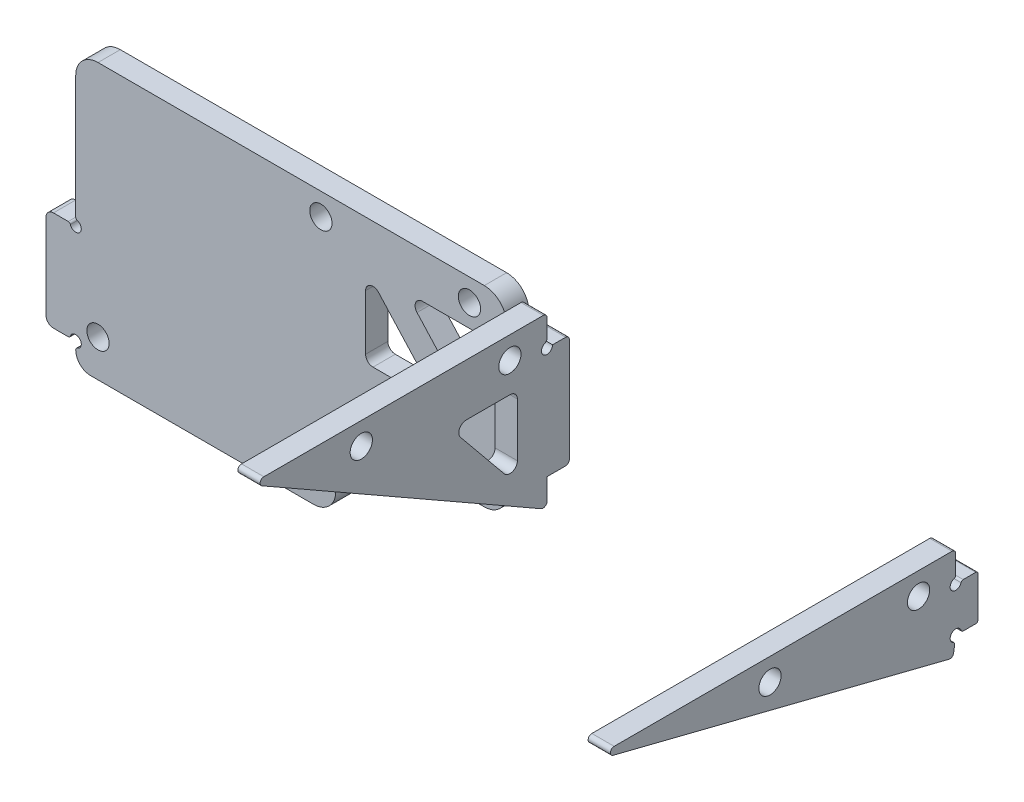
SolidWorks part; units mm, degrees
ref_plane "前视基准面" through (0, 0, 0) normal (0, 0, 1) x (1, 0, 0)
ref_plane "上视基准面" through (0, 0, 0) normal (0, 1, 0) x (1, 0, 0)
ref_plane "右视基准面" through (0, 0, 0) normal (1, 0, 0) x (0, 0, -1)
sketch "草图1" plane through (0, 0, 0) normal (0, 0, 1) x (1, 0, 0)
  line L6 (0, 0) -> (0, 37)
  line L7 (0, 37) -> (35, 37)
  line L9 (135, 16.4475) -> (135, 0)
  line L10 (135, 0) -> (0, 0)
  line L12 (35, 37) -> (135, 37)
  line L13 (135, 37) -> (135, 16.4475)
  dimension "D1" = 37
  dimension "D2" = 135
  dimension "D3" = 35
extrude "凸台-拉伸2" add sketch "草图1" along normal blind 3
sketch "草图4" plane through (0, 0, 3) normal (0, 0, 1) x (1, 0, 0)
  line L0 (135, 12) -> (35.005, 11)
  line L3 (0, 0) -> (135, 0) construction
  line L4 (35.005, 0) -> (135, 0)
  line L5 (135, 0) -> (135, 12)
  line L9 (35.005, 0) -> (35.005, 11)
  dimension "D1" = 100
  dimension "D2" = 12
  dimension "D3" = 11
extrude "切除-拉伸2" cut sketch "草图4" against normal blind 10
sketch "草图6" plane through (0, 0, 3) normal (0, 0, 1) x (1, 0, 0)
  line L0 (0, 0) -> (35.005, 0) construction
  line L1 (0, 37) -> (0, 0) construction
  circle A0 centre (3, 5) radius 1.5
  dimension "D3" = 3
  dimension "D1" = 5
  dimension "D2" = 3
extrude "切除-拉伸4" cut sketch "草图6" against normal blind 10
fillet "圆角3" radius 2 2 edges at (135, 12, 1.5) (0, 0, 1.5)
sketch "草图17" plane through (0, 0, 3) normal (0, 0, 1) x (1, 0, 0)
  line L0 (0, 25) -> (12.5, 25)
  line L1 (0, 37) -> (0, 2) construction
  line L2 (12.5, 25) -> (12.5, 37)
  line L3 (135, 37) -> (0, 37) construction
  line L4 (12.5, 37) -> (0, 37)
  line L5 (0, 37) -> (0, 25)
  dimension "D1" = 12
  dimension "D2" = 12.5
extrude "切除-拉伸10" cut sketch "草图17" against normal blind 10
sketch "草图18" plane through (0, 0, 3) normal (0, 0, 1) x (1, 0, 0)
  line L0 (0, 16.47) -> (-4, 16.47)
  line L1 (0, 25) -> (0, 2) construction
  line L2 (-4, 16.47) -> (-4, 3.03)
  line L3 (-4, 3.03) -> (0, 3.03)
  line L4 (0, 3.03) -> (0, 16.47)
  line L5 (2, 0) -> (35.005, 0) construction
  line L6 (0, 25) -> (12.5, 25) construction
  dimension "D1" = 3.03
  dimension "D2" = 8.53
  dimension "D3" = 4
extrude "凸台-拉伸3" add sketch "草图18" against normal blind 3
sketch "草图19" plane through (0, 0, 3) normal (0, 0, 1) x (1, 0, 0)
  circle A0 centre (0, 3.03) radius 0.75
  circle A1 centre (0, 16.47) radius 0.75
  dimension "D1" = 1.5
extrude "切除-拉伸11" cut sketch "草图19" against normal blind 3
fillet "圆角6" radius 1 2 edges at (-4, 3.03, 1.5) (-4, 16.47, 1.5)
sketch "草图21" plane through (0, 0, 3) normal (0, 0, 1) x (1, 0, 0)
  line L0 (60.42, 34) -> (60.42, 18.95)
  line L1 (60.42, 18.95) -> (63.45, 18.95)
  line L2 (63.45, 18.95) -> (63.45, 34)
  line L3 (63.45, 34) -> (60.42, 34)
  line L5 (135, 37) -> (12.5, 37) construction
  line L6 (12.5, 25) -> (12.5, 37) construction
  line L7 (115.42, 34) -> (115.42, 27.95)
  line L8 (115.42, 27.95) -> (118.45, 27.95)
  line L9 (118.45, 27.95) -> (118.45, 34)
  line L10 (118.45, 34) -> (115.42, 34)
  circle A0 centre (60.42, 34) radius 0.75
  circle A1 centre (63.45, 34) radius 0.75
  circle A2 centre (60.42, 18.95) radius 0.75
  circle A3 centre (63.45, 18.95) radius 0.75
  circle A4 centre (115.42, 34) radius 0.75
  circle A5 centre (118.45, 34) radius 0.75
  circle A6 centre (115.42, 27.95) radius 0.75
  circle A7 centre (118.45, 27.95) radius 0.75
  dimension "D5" = 1.5
  dimension "D6" = 1.5
  dimension "D7" = 1.5
  dimension "D8" = 1.5
  dimension "D13" = 1.5
  dimension "D2" = 15.05
  dimension "D3" = 3.03
  dimension "D4" = 47.92
  dimension "D9" = 3.03
  dimension "D10" = 3
  dimension "D11" = 6.05
  dimension "D12" = 55
  dimension "D14" = 3
extrude "切除-拉伸12" cut sketch "草图21" against normal blind 10 contours A7 L9 A5 L10 A4 L7 A6 L8 | L10 A4 L7 | L7 A4 L10 | L10 A5 L9 | L9 A5 L10 | L7 A6 L8 | L8 A6 L7 | L9 A7 L8 | L8 A7 L9 | A3 L2 A1 L3 A0 L0 A2 L1 | L0 A2 L1 | L1 A2 L0 | L2 A3 L1 | L1 A3 L2 | L0 A0 L3 | L3 A0 L0 | L2 A1 L3 | L3 A1 L2
sketch "草图22" plane through (63.45, 0, 0) normal (-1, 0, 0) x (0, 0, 1)
  line L0 (0, 33.95) -> (0, 18.95)
  line L1 (3, 19.7) -> (3, 33.25) construction
  line L2 (0, 19.7) -> (0, 18.2) construction
  line L4 (0, 18.95) -> (3, 18.95)
  line L6 (3, 18.2) -> (3, 19.7) construction
  line L7 (3, 18.95) -> (3, 15.15)
  line L8 (0, 33.95) -> (3.01, 33.95)
  line L10 (3.01, 33.95) -> (3.01, 38)
  line L11 (3.01, 38) -> (43.01, 38)
  line L12 (43.01, 38) -> (3, 15.15)
  line L13 (8.01, 35) -> (28.01, 35) construction
  line L15 (0, 18.95) -> (3, 18.95) construction
  circle A0 centre (8.01, 35) radius 1.5
  circle A1 centre (28.01, 35) radius 1.5
  dimension "D5" = 20
  dimension "D6" = 5
  dimension "D7" = 3
  dimension "D1" = 15
  dimension "D2" = 40
  dimension "D3" = 3.8
  dimension "D4" = 3
  dimension "D8" = 4.05
  dimension "D9" = 3.01
extrude "凸台-拉伸4" add sketch "草图22" along normal blind 3 separate body
sketch "草图23" plane through (118.45, 0, 0) normal (-1, 0, 0) x (0, 0, 1)
  line L0 (0, 33.95) -> (0, 27.95)
  line L1 (0, 34.75) -> (0, 33.25) construction
  line L2 (0, 13.9801) -> (0, 37) construction
  line L3 (0, 27.95) -> (3, 27.95) construction
  line L4 (0, 28.7) -> (0, 27.2) construction
  line L5 (0, 27.95) -> (3, 27.95)
  line L7 (3, 27.95) -> (3.3598, 25.476)
  line L8 (0, 33.95) -> (3, 33.95)
  line L9 (3, 33.25) -> (3, 34.75) construction
  line L10 (3, 13.9801) -> (3, 37) construction
  line L11 (3, 33.95) -> (3, 38)
  line L12 (3, 38) -> (53, 38)
  line L13 (53, 38) -> (3.3598, 25.476)
  line L14 (3, 27.2) -> (3, 28.7) construction
  line L16 (8, 35) -> (28, 35) construction
  circle A0 centre (8, 35) radius 1.5
  circle A1 centre (28, 35) radius 1.5
  dimension "D5" = 20
  dimension "D6" = 5
  dimension "D7" = 3
  dimension "D1" = 50
  dimension "D2" = 4.05
  dimension "D3" = 6
  dimension "D4" = 2.5
  dimension "D8" = 3
  dimension "D9" = 51.1957
extrude "凸台-拉伸5" add sketch "草图23" along normal blind 3 separate body
fillet "圆角8" radius 0.5 3 edges at (116.95, 38, 3) (116.95, 25.476, 3.3598) (116.95, 38, 53)
sketch "草图25" plane through (60.45, 0, 0) normal (-1, 0, 0) x (0, 0, 1)
  line L0 (7, 31) -> (7, 20)
  line L1 (7, 20) -> (16, 31)
  line L2 (16, 31) -> (7, 31)
  line L6 (8.01, 35) -> (28.01, 35) construction
  line L7 (3, 25) -> (3, 37) construction
  dimension "D1" = 4
  dimension "D4" = 4
  dimension "D6" = 11
  dimension "D7" = 9
extrude "切除-拉伸14" cut sketch "草图25" against normal blind 3
fillet "圆角10" radius 1 3 edges at (61.95, 20, 7) (61.95, 31, 16) (61.95, 31, 7)
sketch "草图28" plane through (60.45, 0, 0) normal (-1, 0, 0) x (0, 0, 1)
  line L0 (3, 18.95) -> (3, 15.15) construction
  circle A0 centre (3.01, 33.95) radius 0.75
  circle A1 centre (3, 14.92) radius 0.75
  dimension "D1" = 1.5
  dimension "D2" = 1.5
  dimension "D3" = 19.03
extrude "切除-拉伸17" cut sketch "草图28" against normal blind 10
sketch "草图29" plane through (118.45, 0, 0) normal (1, 0, 0) x (0, 0, -1)
  circle A1 centre (-3, 33.95) radius 0.75
  circle A2 centre (-3, 27.95) radius 0.75
  dimension "D1" = 1.5
extrude "切除-拉伸18" cut sketch "草图29" against normal blind 10
fillet "圆角13" radius 0.3 4 edges at (-0.75, 3.03, 1.5) (0, 2.28, 1.5) (-0.75, 16.47, 1.5) (0, 17.22, 1.5)
fillet "圆角17" radius 0.3 6 edges at (116.95, 34.7, 3) (116.95, 27.2078, 3.1079) (116.95, 27.95, 2.25) (116.95, 33.95, 0) (116.95, 33.95, 2.25) (116.95, 27.95, 0)
sketch "草图30" plane through (0, 0, 3) normal (0, 0, 1) x (1, 0, 0)
  line L0 (133.02, 11.9802) -> (35.005, 11) construction
  line L1 (135, 13.9801) -> (135, 37) construction
  circle A0 centre (110, 18.7503) radius 1.5
  dimension "D1" = 7
  dimension "D2" = 25
  dimension "D3" = 3
extrude "切除-拉伸19" cut sketch "草图30" against normal blind 10
fillet "圆角21" radius 0.3 8 edges at (62.7, 18.95, 1.5) (61.17, 18.95, 1.5) (60.42, 19.7, 1.5) (60.42, 33.25, 1.5) (62.7, 34, 1.5) (63.45, 33.25, 1.5) (63.45, 19.7, 1.5) (61.17, 34, 1.5)
fillet "圆角22" radius 0.3 8 edges at (117.7, 27.95, 1.5) (116.17, 27.95, 1.5) (115.42, 28.7, 1.5) (115.42, 33.25, 1.5) (116.17, 34, 1.5) (117.7, 34, 1.5) (118.45, 28.7, 1.5) (118.45, 33.25, 1.5)
fillet "圆角26" radius 0.5 7 edges at (61.95, 33.95, 0) (61.95, 34.7, 3.01) (61.95, 38, 3.01) (61.95, 15.4519, 3.5287) (61.95, 15.67, 3) (61.95, 18.95, 0) (61.95, 38, 43.01)
sketch "草图35" plane through (0, 0, 3) normal (0, 0, 1) x (1, 0, 0)
  line L0 (39.0142, 31) -> (39.0142, 20)
  line L1 (39.0142, 20) -> (49.0142, 20)
  line L2 (49.0142, 20) -> (39.0142, 31)
  line L3 (44.42, 31) -> (54.42, 31)
  line L4 (54.42, 31) -> (54.42, 20)
  line L5 (54.42, 20) -> (44.42, 31)
  line L6 (60.42, 32.9938) -> (60.42, 19.9562) construction
  line L7 (135, 37) -> (12.5, 37) construction
  dimension "D1" = 6
  dimension "D2" = 6
  dimension "D3" = 10
  dimension "D4" = 4
  dimension "D5" = 11
  dimension "D6" = 10
extrude "切除-拉伸22" cut sketch "草图35" against normal blind 10
sketch "草图36" plane through (0, 0, 3) normal (0, 0, 1) x (1, 0, 0)
  line L0 (100, 34) -> (33, 34) construction
  line L1 (135, 13.9801) -> (135, 37) construction
  line L2 (135, 37) -> (12.5, 37) construction
  circle A0 centre (100, 34) radius 1.5
  circle A1 centre (80, 34) radius 1.5
  circle A2 centre (53, 34) radius 1.5
  circle A3 centre (33, 34) radius 1.5
  dimension "D1" = 3
  dimension "D5" = 3
  dimension "D8" = 3
  dimension "D9" = 3
  dimension "D2" = 35
  dimension "D3" = 3
  dimension "D4" = 20
  dimension "D6" = 27
  dimension "D7" = 20
extrude "切除-拉伸24" cut sketch "草图36" against normal blind 10
sketch "草图37" plane through (0, 0, 3) normal (0, 0, 1) x (1, 0, 0)
  line L0 (0, 25) -> (12.5, 25)
  line L1 (12.5, 25) -> (12.5, 37)
  line L2 (12.5, 37) -> (0, 37)
  line L3 (0, 37) -> (0, 25)
extrude "凸台-拉伸6" add sketch "草图37" against normal blind 3
fillet "圆角27" radius 3 4 edges at (135, 37, 1.5) (35.005, 0, 1.5) (35.005, 11, 1.5) (0, 37, 1.5)
fillet "圆角28" radius 1 6 edges at (44.42, 31, 1.5) (54.42, 20, 1.5) (54.42, 31, 1.5) (39.0142, 20, 1.5) (49.0142, 20, 1.5) (39.0142, 31, 1.5)
sketch "草图39" plane through (0, 0, 3) normal (0, 0, 1) x (1, 0, 0)
  line L0 (58, 37) -> (58, 11.23)
  line L1 (132, 37) -> (3, 37) construction
  line L2 (133.02, 11.9802) -> (37.975, 11.0297) construction
  line L3 (58, 11.23) -> (135, 11.23)
  line L4 (135, 11.23) -> (135, 37)
  line L5 (135, 37) -> (58, 37)
  line L6 (135, 13.9801) -> (135, 34) construction
  circle A0 centre (53, 34) radius 1.5 construction
  dimension "D1" = 5
extrude "切除-拉伸25" cut sketch "草图39" against normal blind 10
fillet "圆角29" radius 3 2 edges at (58, 11.23, 1.5) (58, 37, 1.5)
